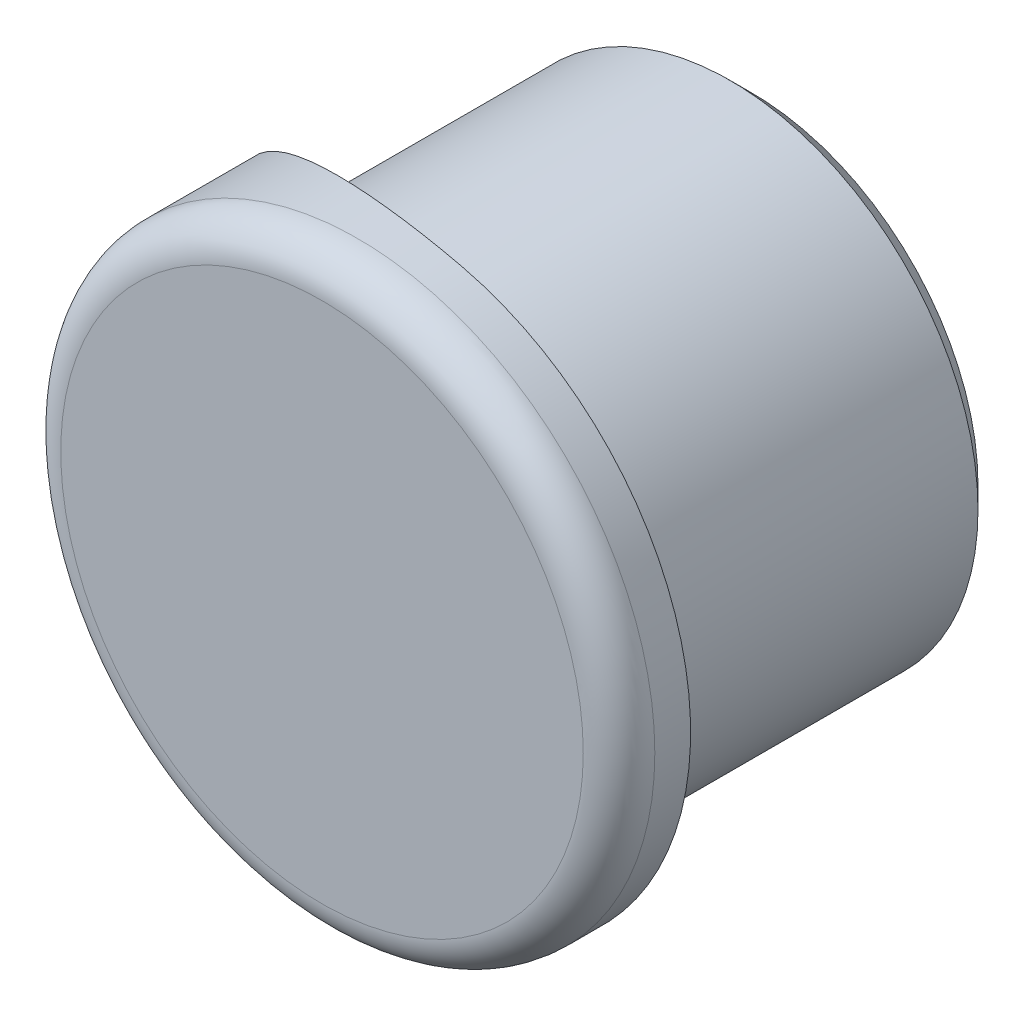
SolidWorks part; units mm, degrees
ref_plane "Plan de face" through (0, 0, 0) normal (0, 0, 1) x (1, 0, 0)
ref_plane "Plan de dessus" through (0, 0, 0) normal (0, 1, 0) x (1, 0, 0)
ref_plane "Plan de droite" through (0, 0, 0) normal (1, 0, 0) x (0, 0, -1)
sketch "Esquisse1" plane through (0, 0, 0) normal (0, 0, 1) x (1, 0, 0)
  circle A0 centre (-38, 67) radius 3.465
  dimension "D1" = 6.93
extrude "Boss.-Extru.1" add sketch "Esquisse1" against normal blind 5
sketch "Esquisse2" plane through (0, 0, 0) normal (0, 0, 1) x (1, 0, 0)
  circle A0 centre (-38, 67) radius 4.15
  dimension "D1" = 8.3
extrude "Boss.-Extru.2" add sketch "Esquisse2" along normal blind 1
fillet "Congé1" radius 0.5 1 edges at (-33.85, 67, 1)
ref_plane "Plan1" through (-41.465, 0, 0) normal (-1, 0, 0) x (0, 0, 1)
ref_plane "Plan2" through (0, 71.15, 0) normal (0, 1, 0) x (1, 0, 0)
sketch "Esquisse4" plane through (29.785, 71.15, 0) normal (0, -1, 0) x (0, 0, 1)
  line L0 (-5, 67.785) -> (1, 67.785) construction
  line L1 (-5, 71.25) -> (-5, 64.32) construction
  line L2 (1, 64.135) -> (1, 71.435) construction
  line L3 (-5, 66.82) -> (0, 66.82) construction
  line L4 (0, 71.25) -> (0, 64.32) construction
  line L5 (0, 71.935) -> (-1.8488, 71.935)
  line L6 (0, 71.935) -> (0, 66.82)
  line L8 (-5, 64.32) -> (0, 64.32) construction
  arc A0 (0, 66.82) -> (-1.8488, 71.935) centre (-8, 66.82) ccw
  dimension "D2" = 8
  dimension "D1" = 2.5
extrude "Boss.-Extru.3" add sketch "Esquisse4" along normal blind 9 and the other way blind 2
sketch "Esquisse5" plane through (0, 0, 1) normal (0, 0, 1) x (1, 0, 0)
  line L0 (-37.035, 62.9638) -> (-36.6285, 58.673)
  line L1 (-36.6285, 58.673) -> (-43.8082, 59.4661)
  line L2 (-43.8082, 59.4661) -> (-42.997, 73.4865)
  line L3 (-42.997, 73.4865) -> (-36.6285, 73.5245)
  line L4 (-36.6285, 73.5245) -> (-37.035, 71.0362)
  arc A0 (-42.15, 67) -> (-37.035, 62.9638) centre (-38, 67) ccw construction
  arc A1 (-42.15, 67) -> (-37.035, 62.9638) centre (-38, 67) ccw
  arc A2 (-37.035, 71.0362) -> (-42.15, 67) centre (-38, 67) ccw construction
  arc A3 (-37.035, 71.0362) -> (-42.15, 67) centre (-38, 67) ccw
extrude "Enlèv. mat.-Extru.1" cut sketch "Esquisse5" against normal blind 4
chamfer "Chanfrein1" distance 0.3 angle 45 1 edges at (-34.535, 67, -5)
sketch "Esquisse7" plane through (0, 0, -5) normal (0, 0, -1) x (-1, 0, 0)
  line L0 (36.7077, 63.785) -> (39.2923, 63.785)
  arc A0 (37.035, 70.3279) -> (37.035, 63.6721) centre (38, 67) ccw construction
  circle A1 centre (38, 67) radius 3.465 construction
  arc A6 (36.7077, 63.785) -> (39.2923, 63.785) centre (38, 67) ccw
  point P2 (38, 63.535)
  dimension "D1" = 0.25
extrude "Enlèv. mat.-Extru.2" cut sketch "Esquisse7" against normal up to surface (4.6749 mm away)
